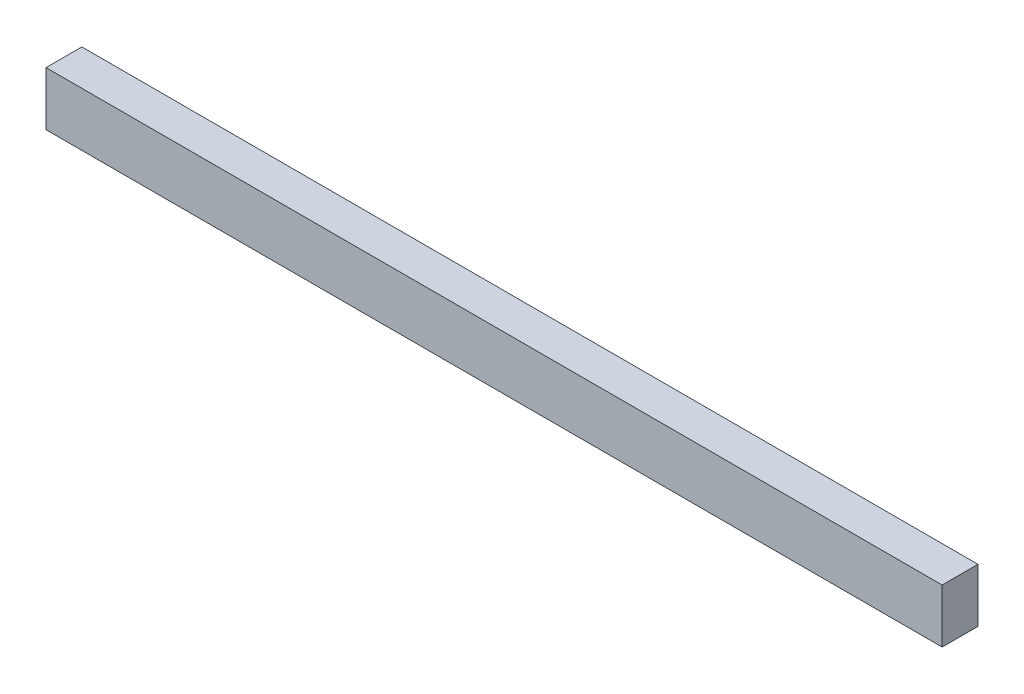
SolidWorks part; units mm, degrees
ref_plane "Front Plane" through (0, 0, 0) normal (0, 0, 1) x (1, 0, 0)
ref_plane "Top Plane" through (0, 0, 0) normal (0, 1, 0) x (1, 0, 0)
ref_plane "Right Plane" through (0, 0, 0) normal (1, 0, 0) x (0, 0, -1)
sketch "Sketch2" plane through (0, 0, 0) normal (0, 0, 1) x (1, 0, 0)
  line L1 (0, 0) -> (25, 0)
  line L2 (0, 0) -> (0, 1.5)
  line L3 (0, 1.5) -> (25, 1.5)
  line L4 (25, 0) -> (25, 1.5)
  dimension "D1" = 1.5
  dimension "D2" = 25
extrude "Boss-Extrude1" add sketch "Sketch2" along normal blind 1 contours L2 L1 L4 L3
